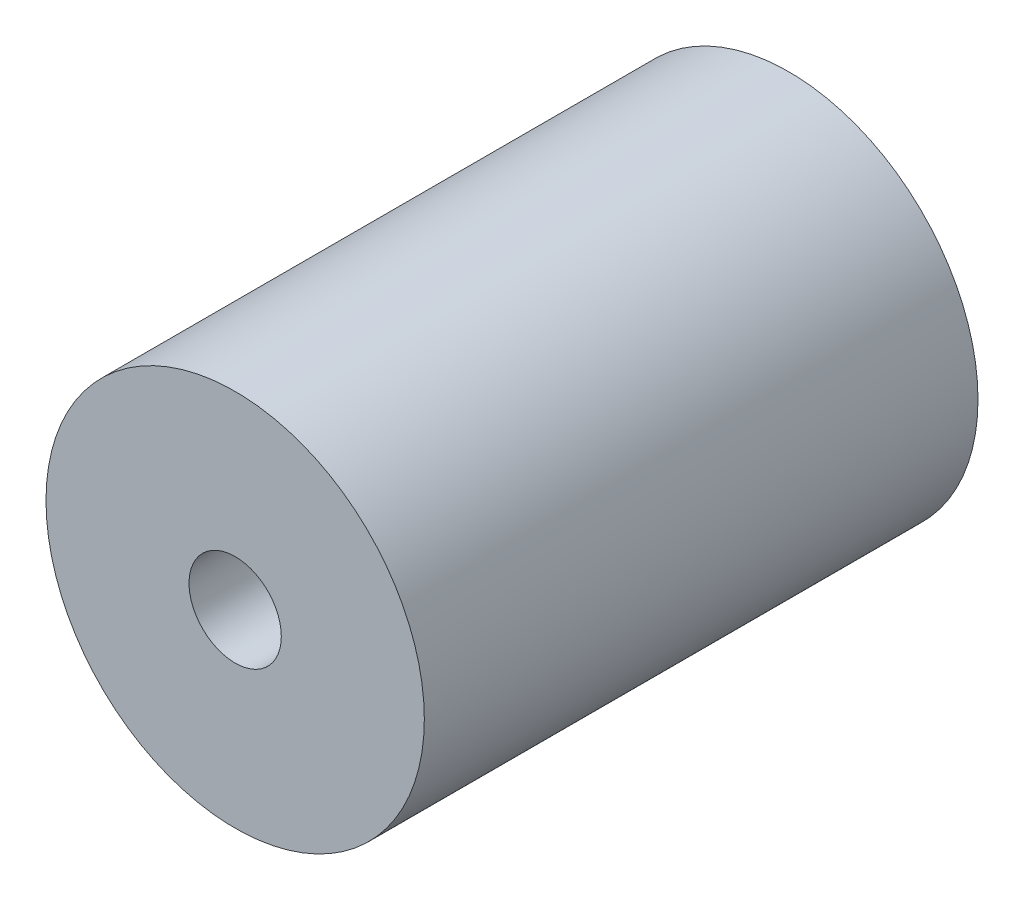
SolidWorks part; units mm, degrees
ref_plane "Alzado" through (0, 0, 0) normal (0, 0, 1) x (1, 0, 0)
ref_plane "Planta" through (0, 0, 0) normal (0, 1, 0) x (1, 0, 0)
ref_plane "Vista lateral" through (0, 0, 0) normal (1, 0, 0) x (0, 0, -1)
sketch "Croquis1" plane through (0, 0, 0) normal (0, 0, 1) x (1, 0, 0)
  circle A0 centre (0, 0) radius 2.5
  circle A1 centre (0, 0) radius 10.25
  dimension "D1" = 5
  dimension "D3" = 20.5
extrude "Saliente-Extruir1" add sketch "Croquis1" along normal blind 15
sketch "Croquis2" plane through (0, 0, 0) normal (0, 0, -1) x (-1, 0, 0)
  circle A1 centre (0, 0) radius 10.25
  circle A2 centre (0, 0) radius 10.25 construction
  circle A3 centre (0, 0) radius 4
  dimension "D1" = 8
extrude "Saliente-Extruir2" add sketch "Croquis2" along normal blind 15
